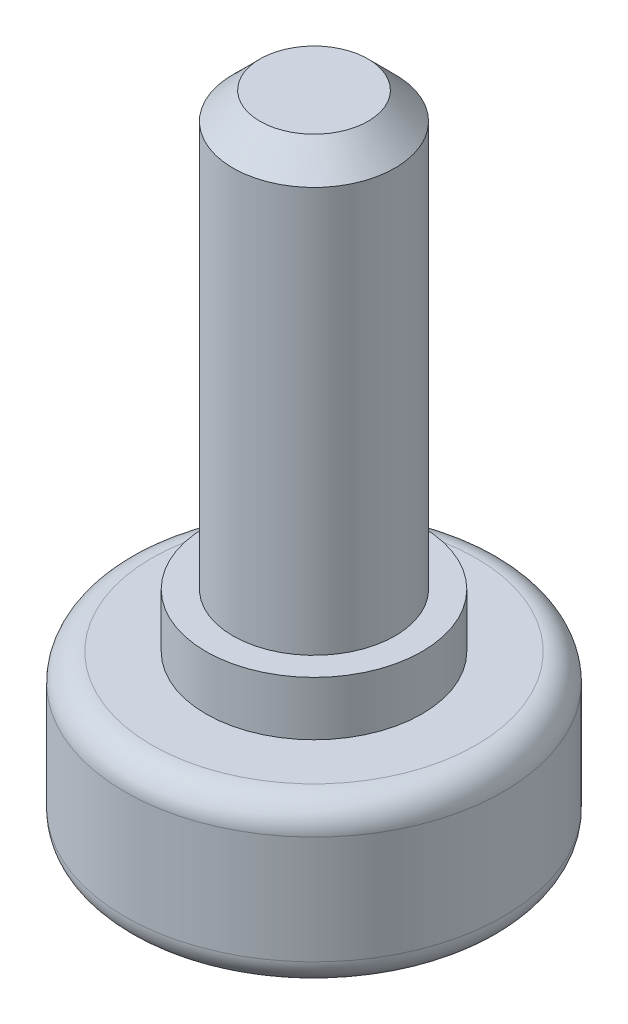
SolidWorks part; units mm, degrees
ref_plane "前视基准面" through (0, 0, 0) normal (0, 0, 1) x (1, 0, 0)
ref_plane "上视基准面" through (0, 0, 0) normal (0, 1, 0) x (1, 0, 0)
ref_plane "右视基准面" through (0, 0, 0) normal (1, 0, 0) x (0, 0, -1)
sketch "草图1" plane through (0, 0, 0) normal (0, 1, 0) x (1, 0, 0)
  circle A0 centre (0, 0) radius 3.5
  dimension "D1" = 7
extrude "凸台-拉伸1" add sketch "草图1" along normal blind 3 contours A0
sketch "草图2" plane through (0, 3, 0) normal (0, 1, 0) x (1, 0, 0)
  circle A0 centre (0, 0) radius 2
  dimension "D1" = 4
extrude "凸台-拉伸2" add sketch "草图2" along normal blind 1
sketch "草图3" plane through (0, 4, 0) normal (0, 1, 0) x (1, 0, 0)
  circle A0 centre (0, 0) radius 1.5
  dimension "D1" = 3
extrude "凸台-拉伸3" add sketch "草图3" along normal blind 8
sketch "草图4" plane through (0, 0, 0) normal (0, -1, 0) x (1, 0, 0)
  circle A0 centre (0, 0) radius 1
  dimension "D1" = 2
extrude "切除-拉伸1" cut sketch "草图4" against normal blind 1.5 contours A0
fillet "圆角1" radius 0.5 2 edges at (0, 0, 3.5) (0, 3, 3.5)
chamfer "倒角1" distance 0.5 angle 45 1 edges at (0, 12, 1.5)
